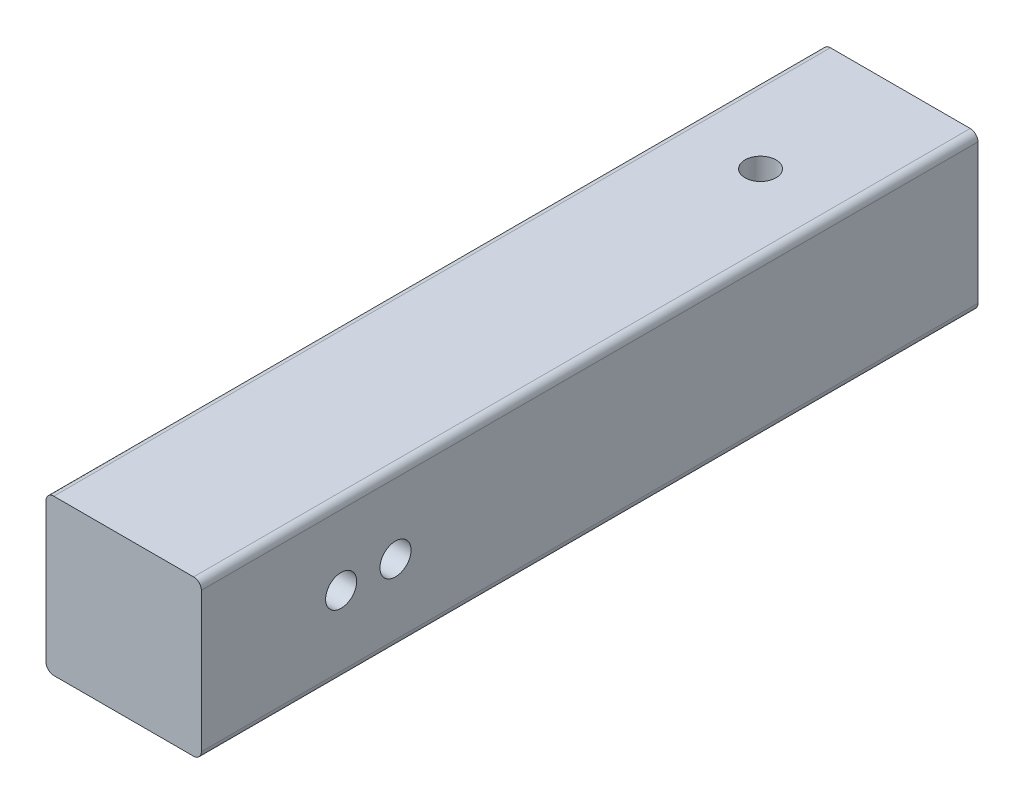
SolidWorks part; units mm, degrees
ref_plane "前视基准面" through (0, 0, 0) normal (0, 0, 1) x (1, 0, 0)
ref_plane "上视基准面" through (0, 0, 0) normal (0, 1, 0) x (1, 0, 0)
ref_plane "右视基准面" through (0, 0, 0) normal (1, 0, 0) x (0, 0, -1)
sketch "草图1" plane through (0, 0, 0) normal (0, 0, 1) x (1, 0, 0)
  line L1 (0, 0) -> (20, 0)
  line L2 (0, 0) -> (0, 20)
  line L3 (0, 20) -> (20, 20)
  line L4 (20, 0) -> (20, 20)
  dimension "D1" = 20
  dimension "D2" = 20
extrude "凸台-拉伸1" add sketch "草图1" along normal blind 100
fillet "圆角1" radius 1 4 edges at (0, 0, 50) (20, 0, 50) (20, 20, 50) (0, 20, 50)
sketch "草图2" plane through (0, 0, 0) normal (-1, 0, 0) x (0, 0, 1)
  line L0 (100, 19) -> (100, 1) construction
  line L1 (0, 20) -> (100, 20) construction
  circle A0 centre (82, 10) radius 2
  dimension "D3" = 4
  dimension "D1" = 18
  dimension "D2" = 10
extrude "切除-拉伸1" cut sketch "草图2" against normal blind 110
sketch "草图3" plane through (0, 20, 0) normal (0, 1, 0) x (1, 0, 0)
  line L0 (19, 0) -> (1, 0) construction
  line L1 (0, -100) -> (0, 0) construction
  circle A0 centre (10, -18) radius 2
  dimension "D3" = 4
  dimension "D1" = 18
  dimension "D2" = 10
extrude "切除-拉伸2" cut sketch "草图3" against normal blind 110
sketch "草图4" plane through (20, 0, 0) normal (1, 0, 0) x (0, 0, -1)
  line L0 (0, 20) -> (-100, 20) construction
  line L1 (-100, 19) -> (-100, 1) construction
  circle A0 centre (-75, 10) radius 2
  point P6 (-37.3278, -38.5583)
  dimension "D3" = 4
  dimension "D1" = 10
  dimension "D2" = 25
extrude "切除-拉伸3" cut sketch "草图4" against normal blind 20
